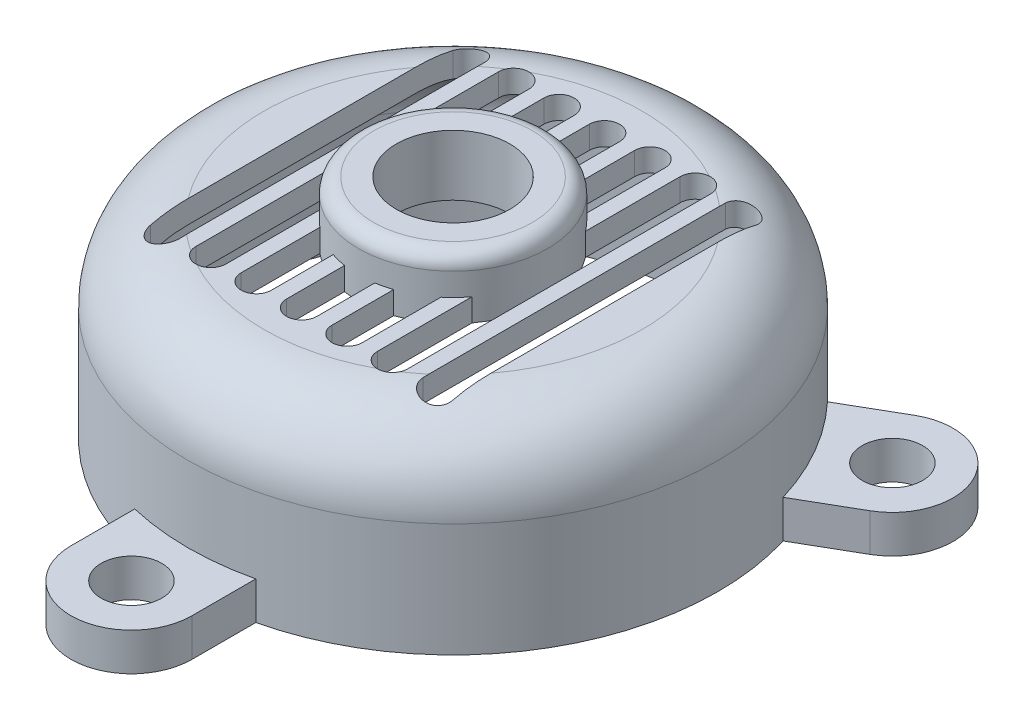
SolidWorks part; units mm, degrees
ref_plane "Front Plane" through (0, 0, 0) normal (0, 0, 1) x (1, 0, 0)
ref_plane "Top Plane" through (0, 0, 0) normal (0, 1, 0) x (1, 0, 0)
ref_plane "Right Plane" through (0, 0, 0) normal (1, 0, 0) x (0, 0, -1)
sketch "Sketch1" plane through (0, 0, 0) normal (0, 1, 0) x (1, 0, 0)
  circle A0 centre (0, 0) radius 35
  dimension "D1" = 70
extrude "Boss-Extrude1" add sketch "Sketch1" along normal blind 25
fillet "Fillet1" radius 10 1 edges at (0, 25, 35)
shell "Shell1" thickness 3
sketch "Sketch2" plane through (0, 0, 0) normal (0, -1, 0) x (1, 0, 0)
  line L2 (-8, 42.5) -> (-8, 32.3995)
  line L3 (-8, 32.3995) -> (8, 32.3995)
  line L4 (8, 42.5) -> (8, 32.3995)
  line L6 (-8, 32.3995) -> (-3.6877, 35.1217) construction
  arc A0 (8, 42.5) -> (-8, 42.5) centre (0, 42.5) ccw
  circle A1 centre (0, 42.5) radius 4
  point P0 (0.3459, 37.6681)
  point P8 (0, 0)
  point P11 (0, 0)
  dimension "D1" = 16
  dimension "D2" = 8
  dimension "D3" = 42.5
extrude "Boss-Extrude2" add sketch "Sketch2" against normal blind 5
pattern_circular "CirPattern1" count 3 over 360 about axis through (0, 0, 0) along (0, 1, 0) of "Boss-Extrude2"
sketch "Sketch3" plane through (0, 25, 0) normal (0, 1, 0) x (1, 0, 0)
  line L0 (-18, 20) -> (-18, -20) construction
  line L1 (-16, 20) -> (-16, -20)
  line L2 (-20, 20) -> (-20, -20)
  arc A0 (-16, 20) -> (-20, 20) centre (-18, 20) ccw
  arc A1 (-20, -20) -> (-16, -20) centre (-18, -20) ccw
  point P2 (-18, 0)
  point P7 (0, 0)
  dimension "D2" = 2
  dimension "D1" = 40
  dimension "D3" = 18
extrude "Cut-Extrude1" cut sketch "Sketch3" against normal through all
sketch "Sketch4" plane through (0, 25, 0) normal (0, 1, 0) x (1, 0, 0)
  line L0 (0, 0) -> (18.3862, 0)
pattern_linear "LPattern1" count 7 spacing 6 along (1, 0, 0) of "Cut-Extrude1"
sketch "Sketch5" plane through (0, 25, 0) normal (0, 1, 0) x (1, 0, 0)
  circle A0 centre (0, 0) radius 7.5
  circle A1 centre (0, 0) radius 12.5
  dimension "D1" = 15
  dimension "D2" = 25
extrude "Boss-Extrude3" add sketch "Sketch5" along normal blind 5 and the other way blind 3
fillet "Fillet2" radius 2 1 edges at (0, 30, 12.5)
sketch "Sketch8" plane through (0, 30, 0) normal (0, 1, 0) x (1, 0, 0)
  circle A0 centre (0, 0) radius 7.5
extrude "Cut-Extrude2" cut sketch "Sketch8" against normal through all both and the other way through all
